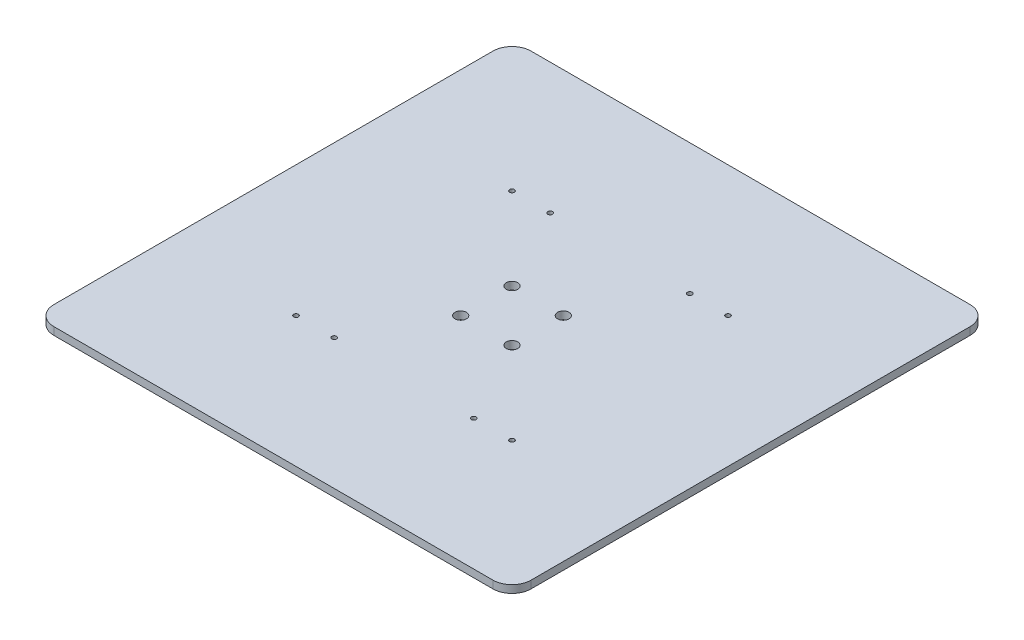
SolidWorks part; units mm, degrees
other "标注1"
sketch "草图10" plane through (-75, 0, -75) normal (0, -1, 0) x (1, 0, 0)
material "AISI 304"
ref_plane "前视基准面" through (0, 0, 0) normal (0, 0, 1) x (1, 0, 0)
ref_plane "上视基准面" through (0, 0, 0) normal (0, 1, 0) x (1, 0, 0)
ref_plane "右视基准面" through (0, 0, 0) normal (1, 0, 0) x (0, 0, -1)
other "Configuration Table"
sketch "草图1" plane through (0, 0, 0) normal (0, 1, 0) x (1, 0, 0)
  line L1 (-125, 125) -> (125, 125)
  line L2 (-125, 125) -> (-125, -125)
  line L3 (-125, -125) -> (125, -125)
  line L4 (125, 125) -> (125, -125)
  line L5 (-125, 125) -> (125, -125) construction
  line L6 (-125, -125) -> (125, 125) construction
  point P0 (0, 0)
  dimension "D1" = 250
  dimension "D2" = 250
extrude "凸台-拉伸1" add sketch "草图1" along normal blind 4
fillet "圆角1" radius 10 4 edges at (-125, 2, 125) (125, 2, 125) (125, 2, -125) (-125, 2, -125)
sketch "草图2" plane through (0, 4, 0) normal (0, 1, 0) x (1, 0, 0)
  line L0 (0, 0) -> (122.0711, 122.0711) construction
  arc A0 (125, 115) -> (115, 125) centre (115, 115) ccw construction
sketch "草图3" plane through (0, 0, 0) normal (0, -1, 0) x (1, 0, 0)
  line L0 (0, 0) -> (122.0711, 122.0711) construction
  arc A0 (125, 115) -> (115, 125) centre (115, 115) ccw construction
  circle A1 centre (56.5685, 56.5685) radius 1.25
  dimension "D1" = 2.5
  dimension "D2" = 80
extrude "切除-拉伸4" cut sketch "草图3" against normal through all
pattern_circular "阵列(圆周)2" count 4 over 360 about axis through (-0.0044, 0, -0.0044) along (0, 1, 0) of "切除-拉伸4"
sketch "草图7" plane through (0, 0, 0) normal (0, -1, 0) x (1, 0, 0)
  line L4 (115, 125) -> (-115, 125)
  line L5 (-125, 115) -> (-125, -115)
  line L6 (-115, -125) -> (115, -125)
  line L7 (125, -115) -> (125, 115)
  line L8 (115, 125) -> (-115, 125)
  line L9 (-125, 115) -> (-125, -115)
  line L10 (-115, -125) -> (115, -125)
  line L11 (125, -115) -> (125, 115)
  circle A0 centre (-56.5774, 56.5685) radius 1.25 construction
  circle A1 centre (-56.5774, -56.5774) radius 1.25 construction
  circle A2 centre (-56.5774, 56.5685) radius 1.25
  circle A3 centre (-56.5774, -56.5774) radius 1.25
  arc A4 (-115, 125) -> (-125, 115) centre (-115, 115) ccw
  arc A5 (-125, -115) -> (-115, -125) centre (-115, -115) ccw
  arc A6 (115, -125) -> (125, -115) centre (115, -115) ccw
  arc A7 (125, 115) -> (115, 125) centre (115, 115) ccw
  arc A8 (-115, 125) -> (-125, 115) centre (-115, 115) ccw
  arc A9 (-125, -115) -> (-115, -125) centre (-115, -115) ccw
  arc A10 (115, -125) -> (125, -115) centre (115, -115) ccw
  arc A11 (125, 115) -> (115, 125) centre (115, 115) ccw
  circle A12 centre (56.5685, 56.5685) radius 1.25 construction
  circle A13 centre (56.5685, -56.5774) radius 1.25 construction
  circle A14 centre (56.5685, 56.5685) radius 1.25
  circle A15 centre (56.5685, -56.5774) radius 1.25
  circle A16 centre (-36.5774, -56.5774) radius 1.25
  circle A17 centre (36.5685, -56.5774) radius 1.25
  circle A18 centre (-36.5774, 56.5685) radius 1.25
  circle A19 centre (36.5685, 56.5685) radius 1.25
  dimension "D1" = 0
  dimension "D2" = 2
  dimension "D3" = 2
  dimension "D4" = 2
  dimension "D5" = 2
extrude "切除-拉伸11" cut sketch "草图7" against normal blind 10 contours A18 | A19 | A16 | A17
sketch "草图9" plane through (0, 0, 0) normal (0, -1, 0) x (1, 0, 0)
  line L0 (-70.1773, 0) -> (106.2684, 0) construction
  line L1 (0, 72.4711) -> (0, -87.6775) construction
  line L2 (0, 0) -> (37.0368, 37.0368) construction
  circle A0 centre (13.435, 13.435) radius 3
  circle A1 centre (13.435, -13.435) radius 3
  circle A2 centre (-13.435, -13.435) radius 3
  circle A3 centre (-13.435, 13.435) radius 3
  point P18 (0, 0)
  dimension "D2" = 6
  dimension "D1" = 45
  dimension "D3" = 19
  dimension "D4" = 4
extrude "切除-拉伸12" cut sketch "草图9" against normal blind 10
